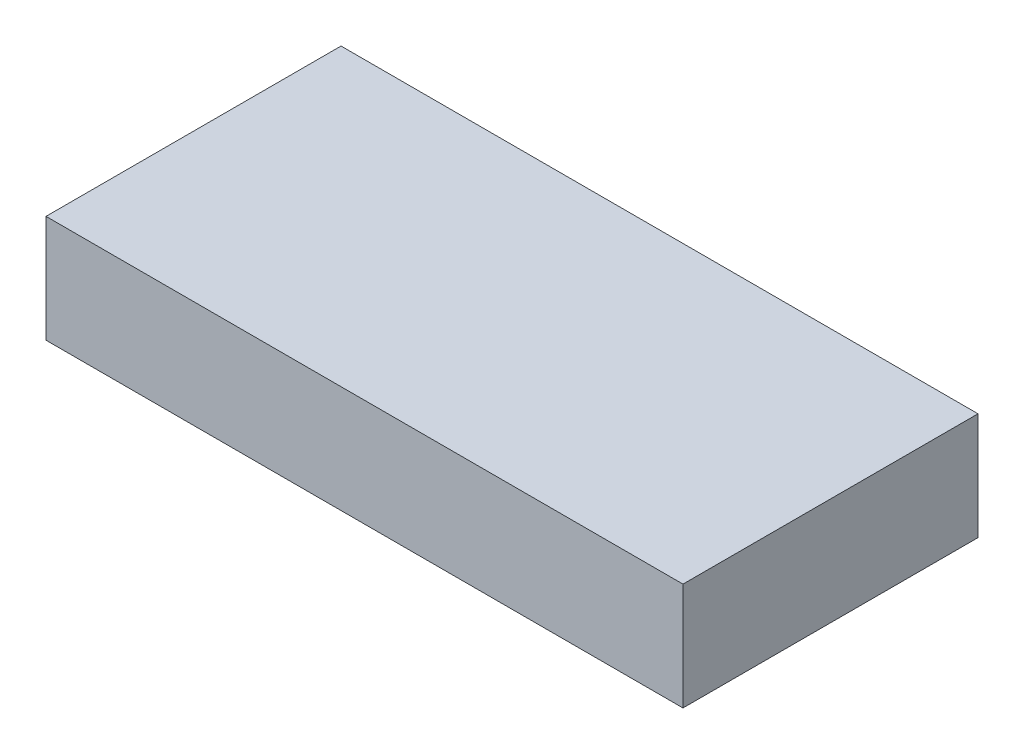
SolidWorks part; units mm, degrees
ref_plane "정면" through (0, 0, 0) normal (0, 0, 1) x (1, 0, 0)
ref_plane "윗면" through (0, 0, 0) normal (0, 1, 0) x (1, 0, 0)
ref_plane "우측면" through (0, 0, 0) normal (1, 0, 0) x (0, 0, -1)
sketch "스케치1" plane through (0, 0, 0) normal (0, 1, 0) x (1, 0, 0)
  line L1 (-47.5, -22) -> (47.5, -22)
  line L2 (-47.5, -22) -> (-47.5, 22)
  line L3 (-47.5, 22) -> (47.5, 22)
  line L4 (47.5, -22) -> (47.5, 22)
  line L5 (-47.5, -22) -> (47.5, 22) construction
  line L6 (-47.5, 22) -> (47.5, -22) construction
  point P0 (0, 0)
  dimension "D1" = 95
  dimension "D2" = 44
extrude "보스-돌출1" add sketch "스케치1" along normal blind 16
